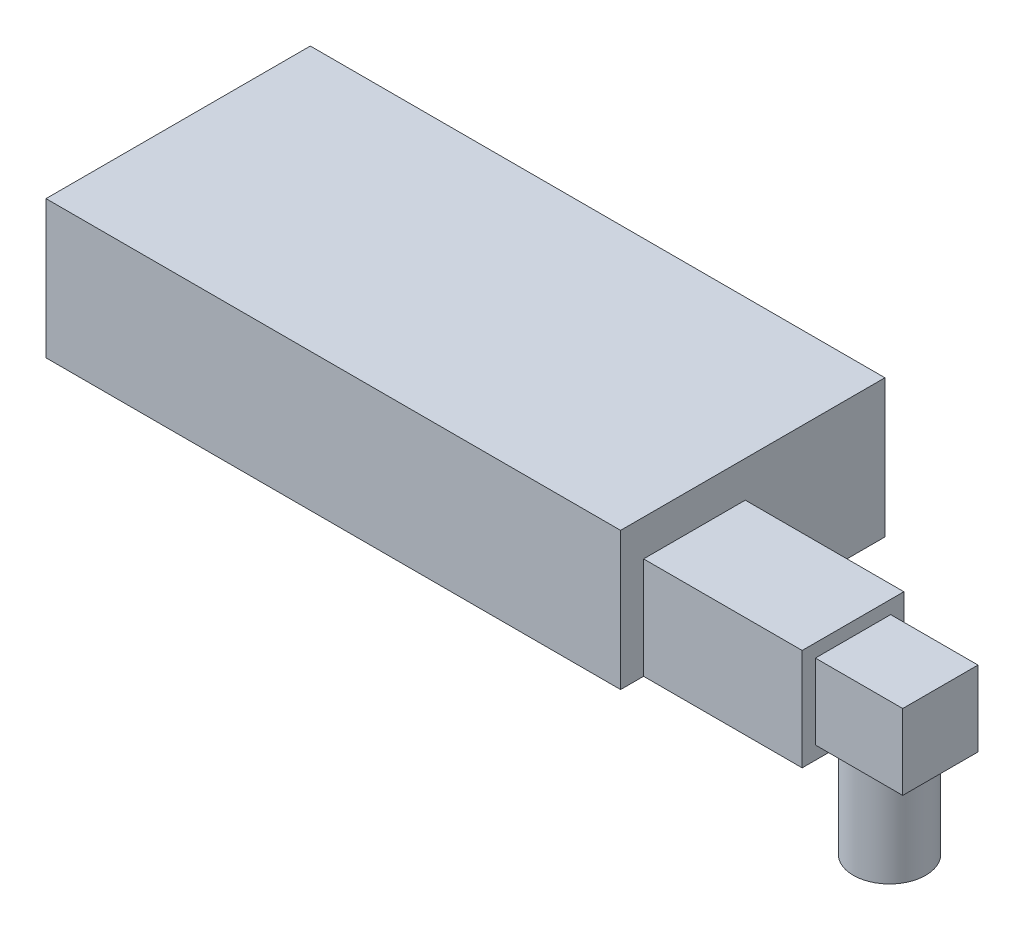
SolidWorks part; units mm, degrees
ref_plane "Front Plane" through (0, 0, 0) normal (0, 0, 1) x (1, 0, 0)
ref_plane "Top Plane" through (0, 0, 0) normal (0, 1, 0) x (1, 0, 0)
ref_plane "Right Plane" through (0, 0, 0) normal (1, 0, 0) x (0, 0, -1)
sketch "Sketch1" plane through (0, 0, 0) normal (0, 1, 0) x (1, 0, 0)
  line L1 (-25, 11.5) -> (25, 11.5)
  line L2 (-25, 11.5) -> (-25, -11.5)
  line L3 (-25, -11.5) -> (25, -11.5)
  line L4 (25, 11.5) -> (25, -11.5)
  line L5 (-25, 11.5) -> (25, -11.5) construction
  line L6 (-25, -11.5) -> (25, 11.5) construction
  point P0 (0, 0)
  dimension "D1" = 23
  dimension "D2" = 50
extrude "Boss-Extrude2" add sketch "Sketch1" along normal blind 12
sketch "Sketch2" plane through (25, 0, 0) normal (1, 0, 0) x (0, 0, -1)
  line L0 (-11.5, 0) -> (11.5, 0) construction
  line L1 (-9.5, 0) -> (-0.65, 0)
  line L2 (-9.5, 0) -> (-9.5, 8.85)
  line L3 (-9.5, 8.85) -> (-0.65, 8.85)
  line L4 (-0.65, 0) -> (-0.65, 8.85)
  line L5 (-11.5, 12) -> (-11.5, 0) construction
  dimension "D1" = 8.85
  dimension "D2" = 2
extrude "Boss-Extrude3" add sketch "Sketch2" along normal blind 21.4 separate body
sketch "Sketch4" plane through (46.4, 0, 0) normal (1, 0, 0) x (0, 0, -1)
  line L1 (-8.35, 1.15) -> (-1.8, 1.15)
  line L2 (-8.35, 1.15) -> (-8.35, 7.7)
  line L3 (-8.35, 7.7) -> (-1.8, 7.7)
  line L4 (-1.8, 1.15) -> (-1.8, 7.7)
  line L5 (-5.075, 8.85) -> (-5.075, 0) construction
  line L6 (-0.65, 8.85) -> (-9.5, 8.85) construction
  line L7 (-5.075, 7.7) -> (-5.075, 0) construction
  line L8 (-9.5, 4.425) -> (-0.65, 4.425) construction
  line L9 (-8.35, 4.425) -> (-1.8, 4.425) construction
  line L12 (-9.5, 8.85) -> (-9.5, 0)
  line L13 (-9.5, 0) -> (-0.65, 0)
  line L14 (-0.65, 0) -> (-0.65, 8.85)
  line L15 (-0.65, 8.85) -> (-9.5, 8.85)
  line L16 (-9.5, 8.85) -> (-9.5, 0)
  line L17 (-9.5, 0) -> (-0.65, 0)
  line L18 (-0.65, 0) -> (-0.65, 8.85)
  line L19 (-0.65, 8.85) -> (-9.5, 8.85)
  line M5 (-9.5, 8.85) -> (-9.5, 0)
  line M6 (-9.5, 0) -> (-0.65, 0)
  line M7 (-0.65, 0) -> (-0.65, 8.85)
  line M8 (-0.65, 8.85) -> (-9.5, 8.85)
  dimension "D1" = 6.55
  dimension "D2" = 0
extrude "Cut-Extrude1" cut sketch "Sketch4" against normal blind 7.6 contours L4 L2 L3 M6 M7 M8 M5
sketch "Sketch3" plane through (0, 1.15, 0) normal (0, 1, 0) x (1, 0, 0)
  line L0 (38.8, -9.5) -> (25, -9.5) construction
  line L1 (46.4, -0.65) -> (37.55, -0.65)
  line L2 (46.4, -0.65) -> (46.4, -9.5)
  line L3 (46.4, -9.5) -> (37.55, -9.5)
  line L4 (37.55, -0.65) -> (37.55, -9.5)
  line L5 (41.975, -0.65) -> (41.975, -9.5) construction
  line L6 (37.55, -5.075) -> (46.4, -5.075) construction
  line L7 (46.4, -8.35) -> (46.4, -1.8) construction
  line L8 (38.8, -0.65) -> (25, -0.65) construction
  circle A0 centre (41.975, -5.075) radius 3.15
  dimension "D1" = 6.3
extrude "Boss-Extrude4" add sketch "Sketch3" against normal blind 8.3 contours A0
